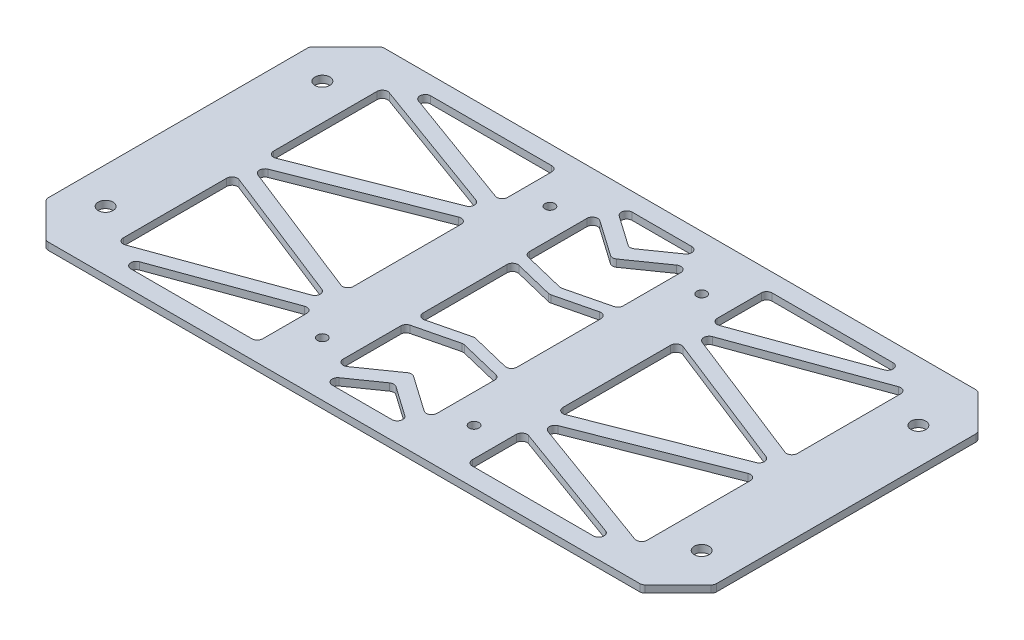
SolidWorks part; units mm, degrees
material "A-玻璃纤维"
ref_plane "前视基准面" through (0, 0, 0) normal (0, 0, 1) x (1, 0, 0)
ref_plane "上视基准面" through (0, 0, 0) normal (0, 1, 0) x (1, 0, 0)
ref_plane "右视基准面" through (0, 0, 0) normal (1, 0, 0) x (0, 0, -1)
sketch "草图1" plane through (0, 0, 0) normal (0, 1, 0) x (1, 0, 0)
  line L0 (-21, 31.5) -> (21, -31.5) construction
  line L1 (-92.5, 46.5) -> (92.5, 46.5)
  line L2 (-92.5, 46.5) -> (-92.5, -46.5)
  line L3 (-92.5, -46.5) -> (92.5, -46.5)
  line L4 (92.5, 46.5) -> (92.5, -46.5)
  line L5 (0, -46.5) -> (0, 46.5) construction
  line L6 (-92.5, 0) -> (92.5, 0) construction
  line L7 (-21, -31.5) -> (21, -31.5) construction
  point P36 (0, 0)
  circle B0 centre (-21, 31.5) radius 1.35
  circle B1 centre (-21, -31.5) radius 1.35
  circle B2 centre (21, -31.5) radius 1.35
  circle B3 centre (21, 31.5) radius 1.35
  dimension "D1" = 185
  dimension "D2" = 15
sketch_block_instance "电源管理孔位-1"
sketch_block "电源管理孔位"
extrude "凸台-拉伸1" add sketch "草图1" along normal blind 2
sketch "草图2" plane through (0, 2, 0) normal (0, 1, 0) x (1, 0, 0)
  line L0 (-82.5, 46.5) -> (-82.5, -46.5) construction
  line L1 (92.5, 46.5) -> (-92.5, 46.5) construction
  line L2 (-92.5, -46.5) -> (92.5, -46.5) construction
  line L3 (0, 29.6184) -> (0, 0) construction
  line L4 (0, 0) -> (30.7992, 0) construction
  line L5 (-92.5, 46.5) -> (-92.5, -46.5) construction
  circle A0 centre (-82.5, 30) radius 2.05
  circle A1 centre (82.5, 30) radius 2.05
  circle A2 centre (82.5, -30) radius 2.05
  circle A3 centre (-82.5, -30) radius 2.05
  dimension "D1" = 4.1
  dimension "D2" = 60
  dimension "D3" = 10
extrude "切除-拉伸1" cut sketch "草图2" against normal blind 20
chamfer "倒角1" distance 10 angle 45 4 edges at (92.5, 1, -46.5) (92.5, 1, 46.5) (-92.5, 1, 46.5) (-92.5, 1, -46.5)
fillet "圆角1" radius 1.5 8 edges at (-82.5, 1, -46.5) (-92.5, 1, -36.5) (-82.5, 1, 46.5) (82.5, 1, 46.5) (92.5, 1, 36.5) (92.5, 1, -36.5) (82.5, 1, -46.5) (-92.5, 1, 36.5)
sketch "草图3" plane through (0, 2, 0) normal (0, 1, 0) x (1, 0, 0)
  line L0 (-92.5, 35.8787) -> (-92.5, -35.8787) construction
  line L1 (-72.5, 41.5) -> (-29, 41.5)
  line L2 (-72.5, 41.5) -> (-72.5, -41.5)
  line L3 (-72.5, -41.5) -> (-29, -41.5)
  line L4 (-29, 41.5) -> (-29, -41.5)
  line L5 (-50.75, -41.5) -> (-50.75, 41.5) construction
  line L6 (-72.5, 0) -> (-29, 0) construction
  line L11 (0, 25.6673) -> (0, 0) construction
  line L12 (72.5, 0) -> (29, 0) construction
  line L17 (50.75, -41.5) -> (50.75, 41.5) construction
  line L18 (72.5, -41.5) -> (29, -25.6673)
  line L20 (81.8787, 46.5) -> (-81.8787, 46.5) construction
  line L21 (-81.8787, -46.5) -> (81.8787, -46.5) construction
  line L22 (-72.5, 41.5) -> (-29, 25.6673)
  line L23 (-72.5, 37.2433) -> (-29, 21.4106)
  line L24 (-29, 21.4106) -> (-72.5, 4.2984)
  line L25 (-72.5, 0) -> (-29, 17.1122)
  line L26 (-72.5, 0) -> (-29, -17.1122)
  line L27 (-29, -21.4106) -> (-72.5, -4.2984)
  line L28 (-72.5, -37.2433) -> (-29, -21.4106)
  line L29 (-72.5, -41.5) -> (-29, -25.6673)
  line L30 (72.5, -37.2433) -> (29, -21.4106)
  line L31 (29, -21.4106) -> (72.5, -4.2984)
  line L32 (72.5, 0) -> (29, -17.1122)
  line L33 (72.5, 0) -> (29, 17.1122)
  line L34 (29, 21.4106) -> (72.5, 4.2984)
  line L35 (72.5, 37.2433) -> (29, 21.4106)
  line L36 (72.5, 41.5) -> (29, 25.6673)
  line L37 (29, 41.5) -> (29, -41.5)
  line L38 (72.5, -41.5) -> (29, -41.5)
  line L41 (72.5, 41.5) -> (72.5, -41.5)
  line L42 (72.5, 41.5) -> (29, 41.5)
  circle A0 centre (-21, 31.5) radius 1.35 construction
  point P44 (50.75, 0)
  point P144 (-50.75, 0)
  dimension "D1" = 20
  dimension "D3" = 8
  dimension "D7" = 5
  dimension "D8" = 5
  dimension "D9" = 4
  dimension "D10" = 4
  dimension "D11" = 70
extrude "切除-拉伸10" cut sketch "草图3" against normal blind 20 contours L1 L22 L4 | L24 L23 L2 | L25 L26 L4 | L2 L28 L27 | L29 L3 L4 | L38 L18 L37 | L41 L31 L30 | L33 L37 L32 | L41 L35 L34 | L36 L42 L37
sketch "草图4" plane through (0, 2, 0) normal (0, 1, 0) x (1, 0, 0)
  line L0 (72.5, 41.5) -> (29, 41.5) construction
  line L1 (-13, 41.5) -> (13, 41.5)
  line L2 (-13, 41.5) -> (-13, -41.5)
  line L3 (-13, -41.5) -> (13, -41.5)
  line L4 (13, 41.5) -> (13, -41.5)
  line L5 (0, -41.5) -> (0, 41.5) construction
  line L6 (-13, 0) -> (13, 0) construction
  line L7 (72.5, -41.5) -> (29, -41.5) construction
  line L8 (-13, -41.5) -> (0, -32.3973)
  line L9 (0, -32.3973) -> (13, -41.5)
  line L10 (-13, -36.6169) -> (0, -27.5142)
  line L11 (0, -27.5142) -> (13, -36.6169)
  line L12 (0, -24.5142) -> (-13, -16.6169)
  line L13 (0, -24.5142) -> (13, -16.6169)
  line L14 (-13, -16.6169) -> (0, -13.4426)
  line L15 (0, -13.4426) -> (13, -16.6169)
  line L16 (-13, -13.5288) -> (0, -10.3544)
  line L17 (0, -10.3544) -> (13, -13.5288)
  line L18 (-13, 0) -> (0, -7.3544)
  line L19 (0, -7.3544) -> (13, 0)
  line L20 (-13, 41.5) -> (0, 32.3973)
  line L21 (0, 32.3973) -> (13, 41.5)
  line L22 (0, 27.5142) -> (13, 36.6169)
  line L23 (-13, 36.6169) -> (0, 27.5142)
  line L24 (0, 24.5142) -> (13, 16.6169)
  line L25 (0, 24.5142) -> (-13, 16.6169)
  line L26 (-13, 16.6169) -> (0, 13.4426)
  line L27 (0, 13.4426) -> (13, 16.6169)
  line L28 (0, 10.3544) -> (13, 13.5288)
  line L29 (-13, 13.5288) -> (0, 10.3544)
  line L30 (0, 7.3544) -> (13, 0)
  line L31 (-13, 0) -> (0, 7.3544)
  circle A0 centre (21, -31.5) radius 1.35 construction
  point P84 (0, 0)
  dimension "D1" = 8
  dimension "D2" = 35
  dimension "D3" = 4
  dimension "D4" = 3
  dimension "D5" = 3
  dimension "D6" = 45
  dimension "D7" = 20
  dimension "D8" = 3
extrude "切除-拉伸11" cut sketch "草图4" against normal blind 20 contours L20 L21 L1 | L25 L24 L4 L22 L23 L2 | L26 L27 L24 L25 | L2 L31 L30 L4 L28 L29 | L31 L18 L19 L30 | L19 L18 L2 L16 L17 L4 | L15 L14 L12 L13 | L13 L12 L2 L10 L11 L4 | L9 L8 L3
fillet "圆角2" radius 1.5 54 edges at (13, 1, 41.5) (-13, 1, 41.5) (0, 1, 32.3973) (29, 1, 17.1122) (29, 1, -17.1122) (72.5, 1, 0) (29, 1, 41.5) (29, 1, 25.6673) (72.5, 1, 41.5) (29, 1, -25.6673) (29, 1, -41.5) (72.5, 1, 37.2433) (29, 1, 21.4106) (72.5, 1, 4.2984) (72.5, 1, -4.2984) (29, 1, -21.4106) (72.5, 1, -37.2433) (13, 1, -41.5) (0, 1, -32.3973) (-13, 1, -41.5) (0, 1, 13.4426) (13, 1, 16.6169) (13, 1, 36.6169) (0, 1, 27.5142) (-13, 1, 36.6169) (-13, 1, 16.6169) (0, 1, -27.5142) (13, 1, -36.6169) (13, 1, -16.6169) (0, 1, -13.4426) (-13, 1, -16.6169) (-13, 1, -36.6169) (0, 1, -10.3544) (13, 1, -13.5288) (13, 1, 13.5288) (0, 1, 10.3544) (-13, 1, 13.5288) (-13, 1, -13.5288) (72.5, 1, -41.5) (-29, 1, 41.5) (-72.5, 1, 41.5) (-29, 1, 25.6673) (-29, 1, 21.4106) (-72.5, 1, 37.2433) (-72.5, 1, 4.2984) (-29, 1, 17.1122) (-72.5, 1, 0) (-29, 1, -17.1122) (-72.5, 1, -4.2984) (-29, 1, -21.4106) (-72.5, 1, -37.2433) (-29, 1, -41.5) (-29, 1, -25.6673) (-72.5, 1, -41.5)
